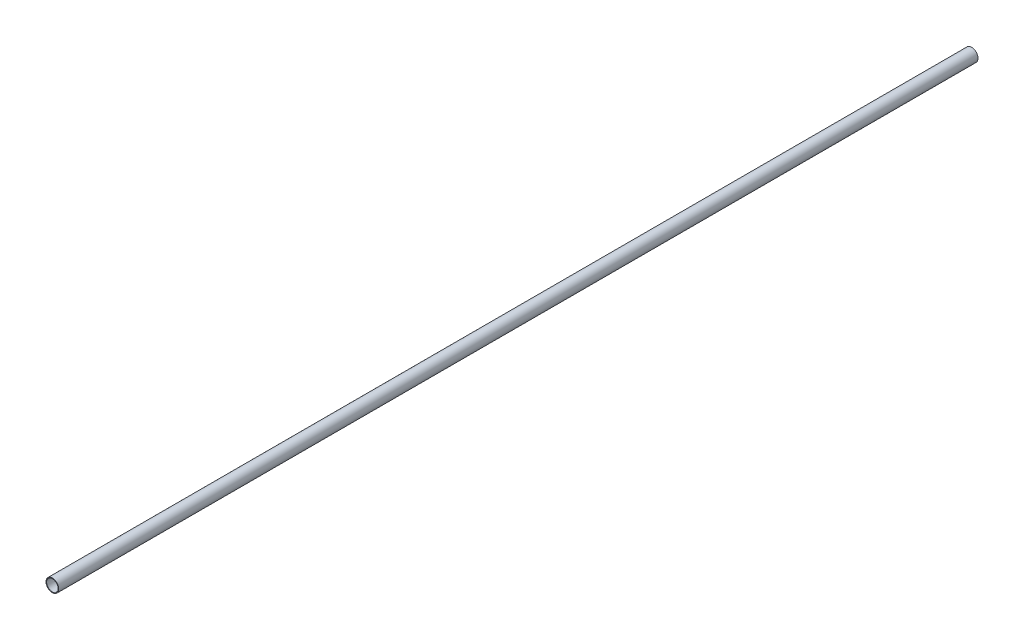
SolidWorks part; units mm, degrees
ref_plane "Front Plane" through (0, 0, 0) normal (0, 0, 1) x (1, 0, 0)
ref_plane "Top Plane" through (0, 0, 0) normal (0, 1, 0) x (1, 0, 0)
ref_plane "Right Plane" through (0, 0, 0) normal (1, 0, 0) x (0, 0, -1)
sketch "Sketch1" plane through (0, 0, 0) normal (0, 0, 1) x (1, 0, 0)
  circle A0 centre (0, 0) radius 12.7 construction
  circle A1 centre (0, 0) radius 11.4554 construction
  point P3 (-12.7, 0)
  point P4 (12.7, 0)
  point P6 (-11.4554, 0)
  point P7 (11.4554, 0)
  dimension "OD" = 25.4
  dimension "Wall" = 1.2446
  dimension "ID" = 22.9108
sketch "Sketch2" plane through (0, 0, 0) normal (1, 0, 0) x (0, 0, -1)
  line L0 (914.4, 0) -> (-914.4, 0) construction
  line L2 (0, 12.7) -> (0, -12.7) construction
  line L3 (0, 12.7) -> (0, -12.7) construction
  line L4 (914.4, 12.7) -> (-914.4, 12.7) construction
  line L5 (914.4, -12.7) -> (-914.4, -12.7) construction
  line L6 (-914.4, -12.7) -> (-914.4, 12.7) construction
  line L7 (914.4, -12.7) -> (914.4, 12.7) construction
  line L8 (-889, -12.7) -> (-889, 12.7) construction
  line L9 (889, -12.7) -> (889, 12.7) construction
  point P3 (0, 0)
  point P9 (0, 12.7)
  point P11 (0, -12.7)
  point P13 (-914.4, 0)
  point P14 (914.4, 12.7)
  point P15 (-914.4, -12.7)
  point P16 (-914.4, 12.7)
  point P17 (-914.4, 0)
  point P18 (914.4, -12.7)
  point P19 (914.4, 0)
  point P22 (-889, 0)
  point P25 (889, 0)
  point P26 (-889, -12.7)
  point P27 (-889, 12.7)
  point P28 (889, 12.7)
  point P29 (889, -12.7)
  dimension "Length" = 1828.8
  dimension "D1" = 25.4
sketch "Sketch3" plane through (0, 0, 0) normal (0, 0, 1) x (1, 0, 0)
  circle A0 centre (0, 0) radius 12.7 construction
  circle A1 centre (0, 0) radius 11.4554 construction
  circle A2 centre (0, 0) radius 12.7
  circle A3 centre (0, 0) radius 11.4554
extrude "Boss-Extrude1" add sketch "Sketch3" along normal mid plane 1828.8
equation "\"D1@Sketch2\"=\"OD@Sketch1\""
equation "\"D1@Boss-Extrude1\"=\"Length@Sketch2\""
